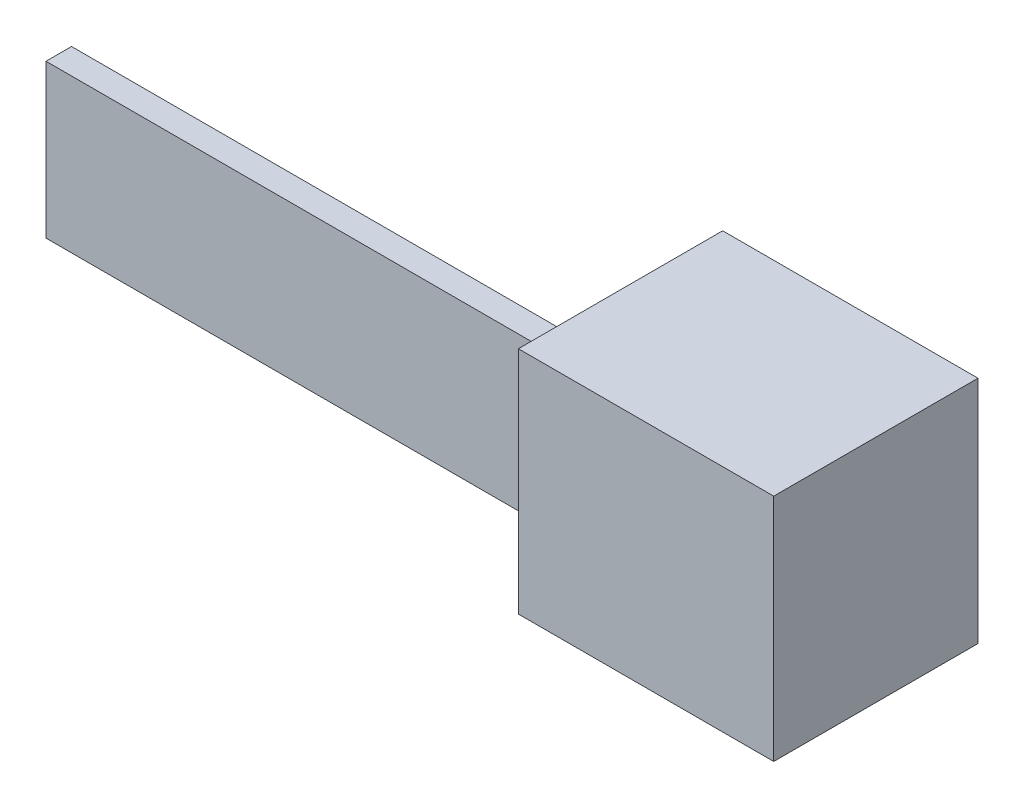
SolidWorks part; units mm, degrees
ref_plane "Front Plane" through (0, 0, 0) normal (0, 0, 1) x (1, 0, 0)
ref_plane "Top Plane" through (0, 0, 0) normal (0, 1, 0) x (1, 0, 0)
ref_plane "Right Plane" through (0, 0, 0) normal (1, 0, 0) x (0, 0, -1)
sketch "Sketch1" plane through (0, 0, 0) normal (0, 1, 0) x (1, 0, 0)
  line L1 (0, -4) -> (10, -4)
  line L2 (0, -4) -> (0, 4)
  line L3 (0, 4) -> (10, 4)
  line L4 (10, -4) -> (10, 4)
  line L5 (0, 0.5) -> (-22, 0.5)
  line L6 (0, 0.5) -> (0, -0.5)
  line L7 (0, -0.5) -> (-22, -0.5)
  line L8 (-22, 0.5) -> (-22, -0.5)
  line L9 (-11, -0.5) -> (-11, 0.5) construction
  line L10 (0, 0) -> (-22, 0) construction
  point P85 (-11, 0)
  dimension "D1" = 32
  dimension "D2" = 1
  dimension "D3" = 8
  dimension "D4" = 10
extrude "Boss-Extrude1" add sketch "Sketch1" along normal mid plane 6 contours L5 L8 L7 L2 | L1 L4 L3 L2
sketch "Sketch2" plane through (0, 3, 0) normal (0, 1, 0) x (1, 0, 0)
  line L1 (0, 4) -> (10, 4)
  line L2 (0, 4) -> (0, -4)
  line L3 (0, -4) -> (10, -4)
  line L4 (10, 4) -> (10, -4)
  line L5 (5, -4) -> (5, 4) construction
  line L6 (0, 0) -> (10, 0) construction
  point P108 (5, 0)
extrude "Boss-Extrude2" add sketch "Sketch2" along normal blind 3
